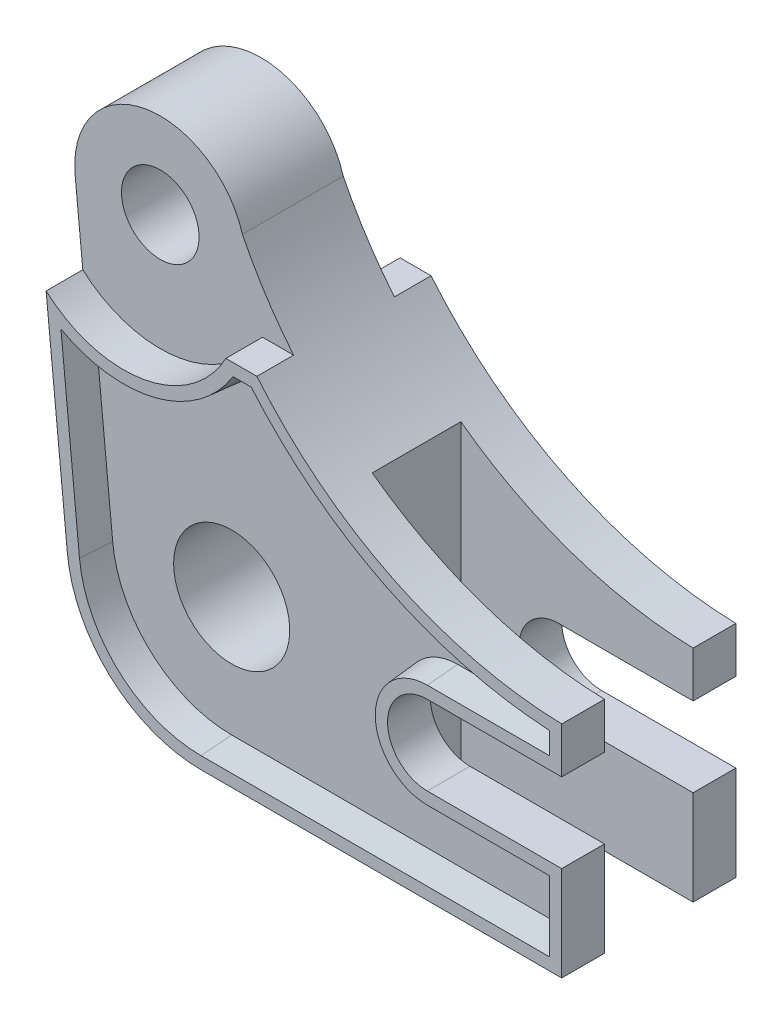
SolidWorks part; units mm, degrees
material "AISI 1020"
ref_plane "Plan de face" through (0, 0, 0) normal (0, 0, 1) x (1, 0, 0)
ref_plane "Plan de dessus" through (0, 0, 0) normal (0, 1, 0) x (1, 0, 0)
ref_plane "Plan de droite" through (0, 0, 0) normal (1, 0, 0) x (0, 0, -1)
sketch "Esquisse1" plane through (0, 0, 0) normal (0, 0, 1) x (1, 0, 0)
  line L0 (-86.6333, -6.9931) -> (-81.9129, -55.1046)
  line L5 (-1.018, -46.4564) -> (-23.018, -46.4564)
  line L7 (-23.018, -59.4564) -> (-1.018, -59.4564)
  line L8 (-1.018, -59.4564) -> (-1.018, -74.9564)
  line L9 (-1.018, -74.9564) -> (-60.018, -74.9564)
  line L13 (-60.018, -52.9564) -> (-60.018, -14.6646) construction
  line L14 (-60.018, -52.9564) -> (-72.7002, -5.6261) construction
  line L15 (-1.018, -46.4564) -> (-1.018, -38.9564)
  arc A0 (-81.9129, -55.1046) -> (-60.018, -74.9564) centre (-60.018, -52.9564) ccw
  arc A3 (-23.018, -59.4564) -> (-23.018, -46.4564) centre (-23.018, -52.9564) cw
  circle A4 centre (-72.7002, -5.6261) radius 6.35
  circle A5 centre (-60.018, -52.9564) radius 9.5
  arc A7 (-1.018, -38.9564) -> (-59.2631, -1.6959) centre (0.7869, 28.0193) cw
  arc A8 (-59.2631, -1.6959) -> (-86.6333, -6.9931) centre (-72.7002, -5.6261) ccw
  point P2 (-47.7667, -14.6646)
  point P3 (0, 0)
  point P12 (-86.6333, -6.9931)
  point P13 (0, 0)
  dimension "D1" = 22
  dimension "D3" = 6.5
  dimension "D4" = 14
  dimension "D10" = 67
  dimension "D15" = 12.7
  dimension "D6" = 59
  dimension "D7" = 22
  dimension "D8" = 49
  dimension "D9" = 0
  dimension "D11" = 0
  dimension "D5" = 0
  dimension "D12" = 15
  dimension "D13" = 22
  dimension "D14" = 0
  dimension "D2" = 36
extrude "Boss.-Extru.1" add sketch "Esquisse1" along normal blind 28.5
sketch "Esquisse2" plane through (0, 0, 28.5) normal (0, 0, 1) x (1, 0, 0)
  line L0 (-50.8888, -14.6261) -> (-55.967, -14.6261)
  line L2 (-86.6333, -6.9931) -> (-81.9129, -55.1046) construction
  line L3 (-86.6333, -6.9931) -> (-85.379, -19.7769)
  arc A0 (-55.967, -14.6261) -> (-85.379, -19.7769) centre (-72.7002, -5.6261) cw
  arc A2 (-59.2631, -1.6959) -> (-1.018, -38.9564) centre (0.7869, 28.0193) ccw construction
  arc A3 (-59.2631, -1.6959) -> (-86.6333, -6.9931) centre (-72.7002, -5.6261) ccw construction
  arc A4 (-59.2631, -1.6959) -> (-50.8888, -14.6261) centre (0.7869, 28.0193) ccw
  arc A5 (-59.2631, -1.6959) -> (-86.6333, -6.9931) centre (-72.7002, -5.6261) ccw
  point P9 (0, 0)
  point P11 (-70.7189, -7.9477)
  point P12 (0, 0)
  dimension "D1" = 19
  dimension "D2" = 9
extrude "Enlèv. mat.-Extru.1" cut sketch "Esquisse2" against normal blind 6
sketch "Esquisse3" plane through (0, 0, 0) normal (0, 0, -1) x (-1, 0, 0)
  line L2 (85.379, -19.7769) -> (86.6333, -6.9931)
  line L3 (50.8888, -14.6261) -> (55.967, -14.6261)
  line L4 (85.379, -19.7769) -> (86.6333, -6.9931)
  line L5 (50.8888, -14.6261) -> (55.967, -14.6261)
  arc A3 (50.8888, -14.6261) -> (59.2631, -1.6959) centre (-0.7869, 28.0193) ccw
  arc A4 (86.6333, -6.9931) -> (59.2631, -1.6959) centre (72.7002, -5.6261) ccw
  arc A5 (55.967, -14.6261) -> (85.379, -19.7769) centre (72.7002, -5.6261) ccw
  arc A6 (50.8888, -14.6261) -> (59.2631, -1.6959) centre (-0.7869, 28.0193) ccw
  arc A7 (86.6333, -6.9931) -> (59.2631, -1.6959) centre (72.7002, -5.6261) ccw
  arc A8 (55.967, -14.6261) -> (85.379, -19.7769) centre (72.7002, -5.6261) ccw
  dimension "D1" = 0
extrude "Enlèv. mat.-Extru.2" cut sketch "Esquisse3" against normal blind 6
sketch "Esquisse4" plane through (0, -74.9564, 0) normal (0, -1, 0) x (1, 0, 0)
  line L0 (-39.018, 7) -> (-39.018, 21.5)
  line L3 (-1.018, 28.5) -> (-1.018, 0) construction
  line L4 (-39.018, 21.5) -> (-1.018, 21.5)
  line L5 (-39.018, 7) -> (-1.018, 7)
  line L6 (-1.018, 7) -> (-1.018, 21.5)
  line L7 (-1.018, 0) -> (-59.2631, 0) construction
  line L8 (-60.018, 28.5) -> (-1.018, 28.5) construction
  dimension "D1" = 38
  dimension "D2" = 7
  dimension "D3" = 7
extrude "Enlèv. mat.-Extru.3" cut sketch "Esquisse4" against normal through all
sketch "Esquisse5" plane through (0, 0, 28.5) normal (0, 0, 1) x (1, 0, 0)
  line L7 (-51.8229, -16.6261) -> (-54.8116, -16.6261)
  line L8 (-82.9601, -23.9491) -> (-79.9225, -54.9093)
  line L9 (-60.018, -72.9564) -> (-3.018, -72.9564)
  line L10 (-3.018, -72.9564) -> (-3.018, -61.4564)
  line L11 (-3.018, -61.4564) -> (-23.018, -61.4564)
  line L12 (-23.018, -44.4564) -> (-3.018, -44.4564)
  line L13 (-3.018, -44.4564) -> (-3.018, -40.8757)
  line L14 (-50.8888, -14.6261) -> (-55.967, -14.6261)
  line L15 (-85.379, -19.7769) -> (-81.9129, -55.1046)
  line L16 (-60.018, -74.9564) -> (-1.018, -74.9564)
  line L17 (-1.018, -74.9564) -> (-1.018, -59.4564)
  line L18 (-1.018, -59.4564) -> (-23.018, -59.4564)
  line L19 (-23.018, -46.4564) -> (-1.018, -46.4564)
  line L20 (-1.018, -46.4564) -> (-1.018, -38.9564)
  line L21 (-50.8888, -14.6261) -> (-55.967, -14.6261)
  line L22 (-85.379, -19.7769) -> (-81.9129, -55.1046)
  line L23 (-60.018, -74.9564) -> (-1.018, -74.9564)
  line L24 (-1.018, -74.9564) -> (-1.018, -59.4564)
  line L25 (-1.018, -59.4564) -> (-23.018, -59.4564)
  line L26 (-23.018, -46.4564) -> (-1.018, -46.4564)
  line L27 (-1.018, -46.4564) -> (-1.018, -38.9564)
  arc A4 (-82.9601, -23.9491) -> (-54.8116, -16.6261) centre (-72.7002, -5.6261) ccw
  arc A5 (-79.9225, -54.9093) -> (-60.018, -72.9564) centre (-60.018, -52.9564) ccw
  arc A6 (-23.018, -44.4564) -> (-23.018, -61.4564) centre (-23.018, -52.9564) ccw
  arc A7 (-51.8229, -16.6261) -> (-3.018, -40.8757) centre (0.7869, 28.0193) ccw
  arc A8 (-85.379, -19.7769) -> (-55.967, -14.6261) centre (-72.7002, -5.6261) ccw
  arc A9 (-81.9129, -55.1046) -> (-60.018, -74.9564) centre (-60.018, -52.9564) ccw
  arc A10 (-23.018, -46.4564) -> (-23.018, -59.4564) centre (-23.018, -52.9564) ccw
  arc A11 (-50.8888, -14.6261) -> (-1.018, -38.9564) centre (0.7869, 28.0193) ccw
  arc A12 (-85.379, -19.7769) -> (-55.967, -14.6261) centre (-72.7002, -5.6261) ccw
  arc A13 (-81.9129, -55.1046) -> (-60.018, -74.9564) centre (-60.018, -52.9564) ccw
  arc A14 (-23.018, -46.4564) -> (-23.018, -59.4564) centre (-23.018, -52.9564) ccw
  arc A15 (-50.8888, -14.6261) -> (-1.018, -38.9564) centre (0.7869, 28.0193) ccw
  dimension "D1" = 0
  dimension "D2" = 2
extrude "Enlèv. mat.-Extru.5" cut sketch "Esquisse5" against normal offset from surface 2 draft 5 contours L7 A4 L8 A5 L9 L10 L11 A6 L12 L13 A7
equation "\"A\"= 59"
equation "\"B\"= 22"
equation "\"C\"= 28.5"
equation "\"D6@Esquisse1\"=\"A\""
equation "\"D1@Esquisse1\"=\"B\""
equation "\"D13@Esquisse1\"=\"B\""
equation "\"D1@Boss.-Extru.1\"=\"C\""
